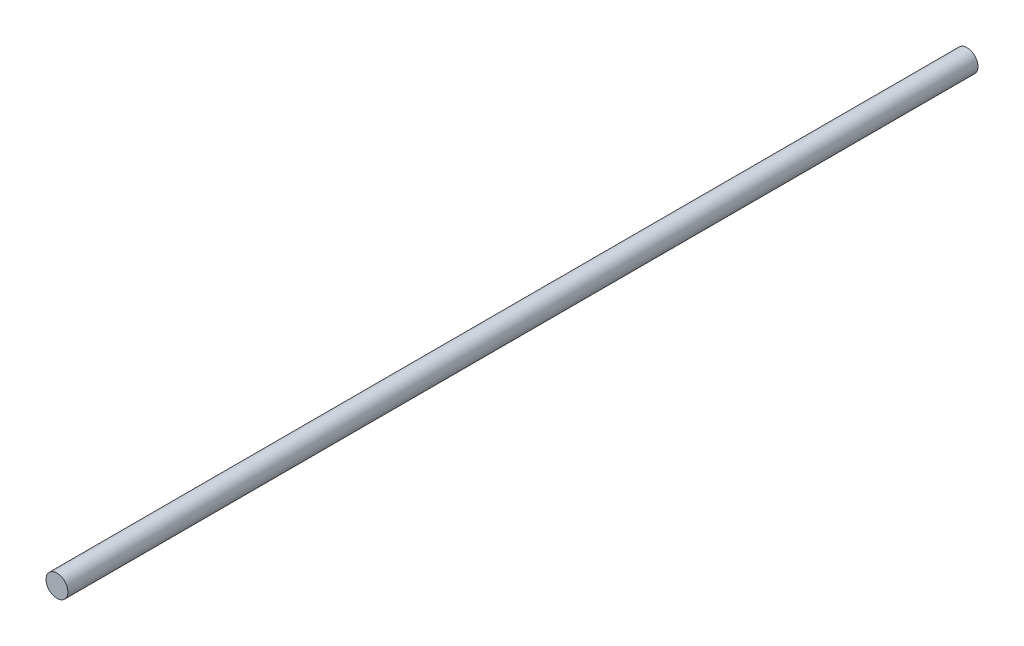
SolidWorks part; units mm, degrees
material "AISI 1045 Steel, cold drawn"
ref_plane "Front Plane" through (0, 0, 0) normal (0, 0, 1) x (1, 0, 0)
ref_plane "Top Plane" through (0, 0, 0) normal (0, 1, 0) x (1, 0, 0)
ref_plane "Right Plane" through (0, 0, 0) normal (1, 0, 0) x (0, 0, -1)
sketch "Sketch1" plane through (0, 0, 0) normal (0, 0, 1) x (1, 0, 0)
  circle A0 centre (0, 0) radius 6.35
  dimension "D1" = 12.7
extrude "Boss-Extrude1" add sketch "Sketch1" along normal blind 527.05
